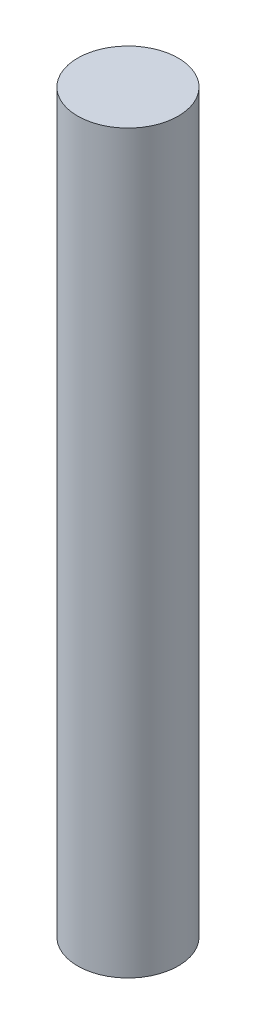
SolidWorks part; units mm, degrees
material "ABS"
ref_plane "Front Plane" through (0, 0, 0) normal (0, 0, 1) x (1, 0, 0)
ref_plane "Top Plane" through (0, 0, 0) normal (0, 1, 0) x (1, 0, 0)
ref_plane "Right Plane" through (0, 0, 0) normal (1, 0, 0) x (0, 0, -1)
sketch "Sketch2" plane through (0, 0, 0) normal (0, 1, 0) x (1, 0, 0)
  circle A0 centre (0, 0) radius 2.05
extrude "Boss-Extrude1" add sketch "Sketch2" along normal blind 30
